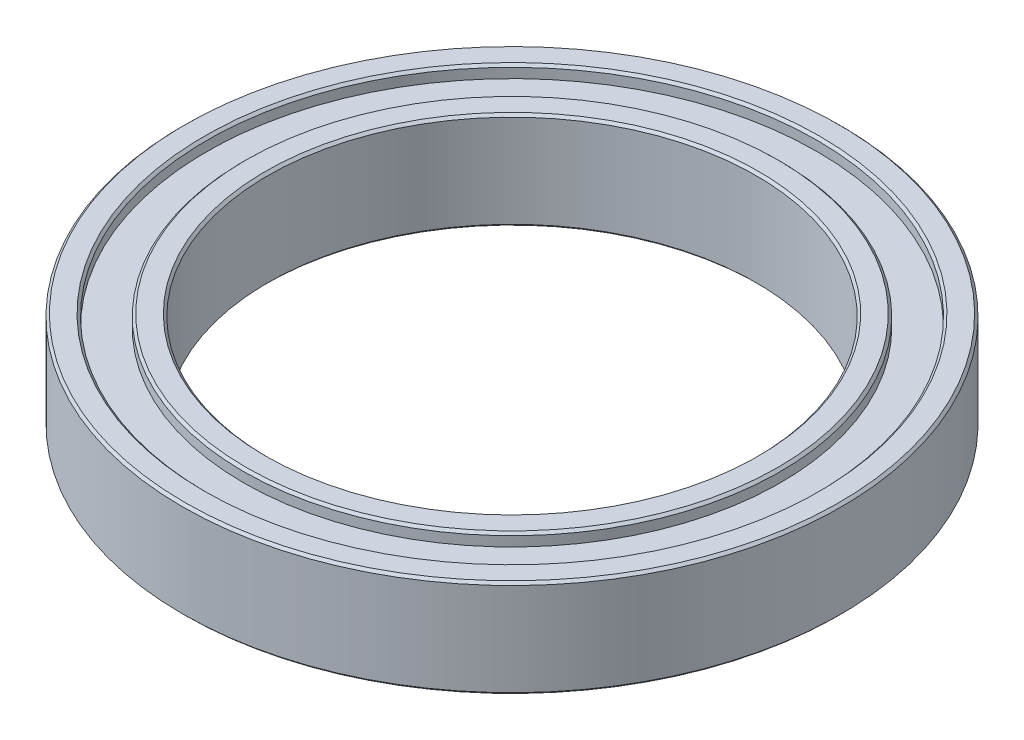
SolidWorks part; units mm, degrees
material "1023 碳钢板 (SS)"
ref_plane "前视基准面" through (0, 0, 0) normal (0, 0, 1) x (1, 0, 0)
ref_plane "上视基准面" through (0, 0, 0) normal (0, 1, 0) x (1, 0, 0)
ref_plane "右视基准面" through (0, 0, 0) normal (1, 0, 0) x (0, 0, -1)
sketch "草图1" plane through (0, 0, 0) normal (0, 1, 0) x (1, 0, 0)
  circle A0 centre (0, 0) radius 10
  circle A1 centre (0, 0) radius 13.5
  dimension "D1" = 27
  dimension "D2" = 20
extrude "凸台-拉伸1" add sketch "草图1" along normal blind 4
sketch "草图2" plane through (0, 4, 0) normal (0, 1, 0) x (1, 0, 0)
  circle A0 centre (0, 0) radius 11
  circle A1 centre (0, 0) radius 12.5
  circle A2 centre (0, 0) radius 13.5 construction
  circle A3 centre (0, 0) radius 10 construction
  dimension "D1" = 0
  dimension "D2" = 1
  dimension "D3" = 1
extrude "切除-拉伸1" cut sketch "草图2" against normal blind 0.5 contours A1
ref_plane "基准面1" through (0, 2, 0) normal (0, 1, 0) x (1, 0, 0)
mirror "镜向1" about plane through (0, 2, 0) normal (0, 1, 0) of "切除-拉伸1"
chamfer "倒角1" distance 0.1 angle 45 8 edges at (0, 0, 10) (0, 0, 11) (0, 0, 12.5) (0, 0, 13.5) (0, 4, 10) (0, 4, 11) (0, 4, 12.5) (0, 4, 13.5)
